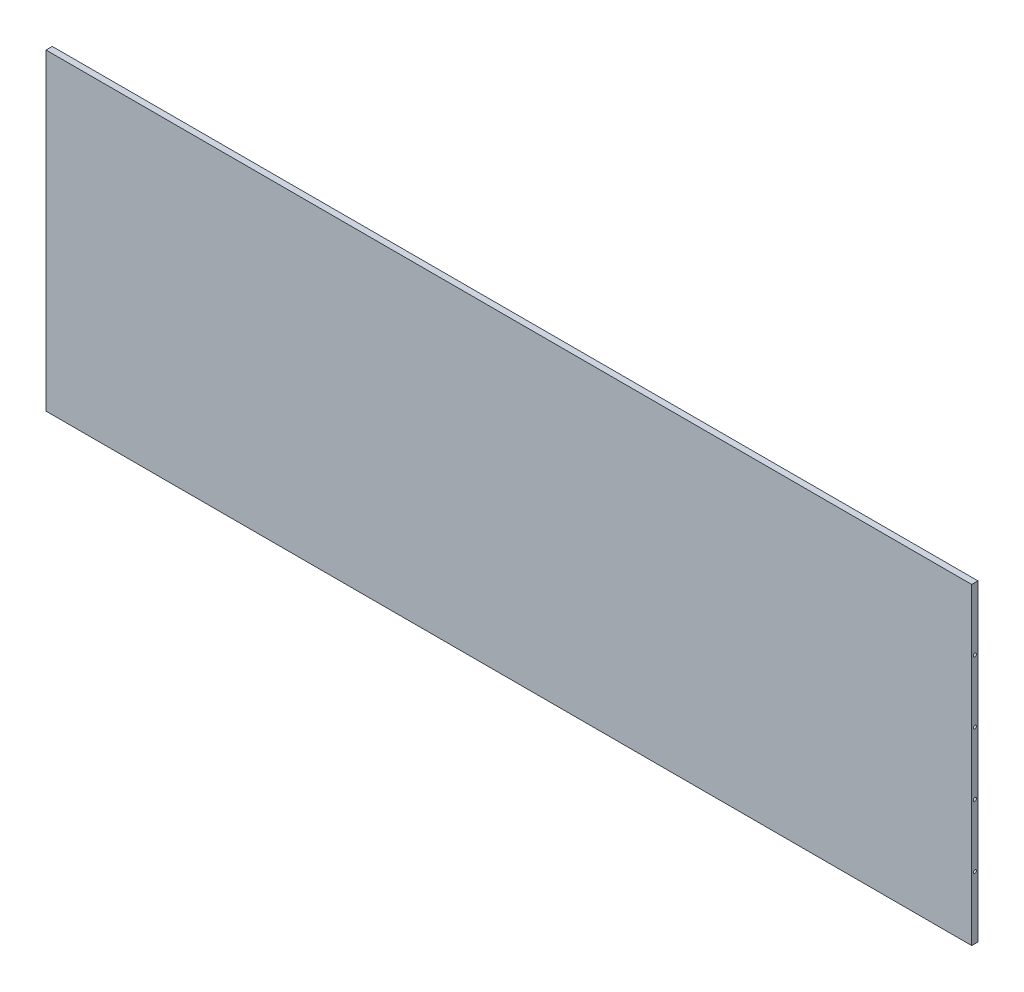
SolidWorks part; units mm, degrees
ref_plane "Alzado" through (0, 0, 0) normal (0, 0, 1) x (1, 0, 0)
ref_plane "Planta" through (0, 0, 0) normal (0, 1, 0) x (1, 0, 0)
ref_plane "Vista lateral" through (0, 0, 0) normal (1, 0, 0) x (0, 0, -1)
sketch "Croquis1" plane through (0, 0, 0) normal (0, 0, 1) x (1, 0, 0)
  line L1 (-740, -250) -> (740, -250)
  line L2 (-740, -250) -> (-740, 250)
  line L3 (-740, 250) -> (740, 250)
  line L4 (740, -250) -> (740, 250)
  line L5 (-740, -250) -> (740, 250) construction
  line L6 (-740, 250) -> (740, -250) construction
  point P0 (0, 0)
  dimension "D1" = 1480
  dimension "D2" = 500
extrude "Saliente-Extruir1" add sketch "Croquis1" along normal mid plane 10
sketch "Croquis2" plane through (0, -250, 0) normal (0, -1, 0) x (1, 0, 0)
  line L0 (-740, 0) -> (740, 0) construction
  line L1 (-740, 5) -> (-740, -5) construction
  line L2 (740, 5) -> (740, -5) construction
  circle A0 centre (-690, 0) radius 2.5
  circle A1 centre (-590, 0) radius 2.5
  circle A2 centre (-490, 0) radius 2.5
  circle A3 centre (-390, 0) radius 2.5
  circle A4 centre (-290, 0) radius 2.5
  circle A5 centre (-190, 0) radius 2.5
  circle A6 centre (-90, 0) radius 2.5
  circle A7 centre (10, 0) radius 2.5
  circle A8 centre (110, 0) radius 2.5
  circle A9 centre (210, 0) radius 2.5
  circle A10 centre (310, 0) radius 2.5
  circle A11 centre (410, 0) radius 2.5
  circle A12 centre (510, 0) radius 2.5
  circle A13 centre (610, 0) radius 2.5
  circle A14 centre (710, 0) radius 2.5
  dimension "D1" = 5
  dimension "D2" = 50
  dimension "D3" = 15
extrude "Cortar-Extruir1" cut sketch "Croquis2" against normal blind 5
sketch "Croquis3" plane through (-740, 0, 0) normal (-1, 0, 0) x (0, 0, 1)
  line L0 (0, -250) -> (0, 250) construction
  line L1 (5, -250) -> (-5, -250) construction
  line L2 (5, 250) -> (-5, 250) construction
  circle A0 centre (0, -150) radius 2.5
  circle A1 centre (0, -50) radius 2.5
  circle A2 centre (0, 50) radius 2.5
  circle A3 centre (0, 150) radius 2.5
  dimension "D1" = 5
  dimension "D2" = 100
  dimension "D3" = 4
extrude "Cortar-Extruir2" cut sketch "Croquis3" against normal blind 5
mirror "Simetría5" about plane through (0, 0, 0) normal (1, 0, 0) of "Cortar-Extruir2"
